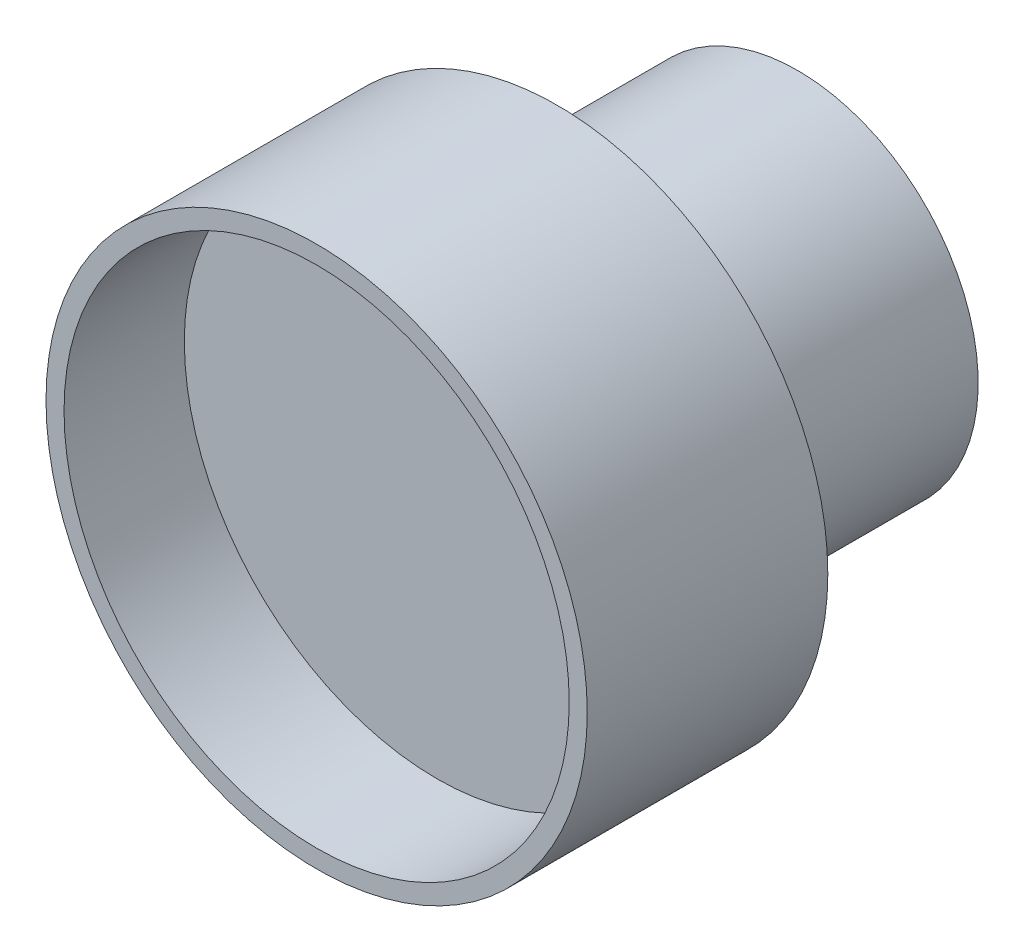
SolidWorks part; units mm, degrees
ref_plane "Front Plane" through (0, 0, 0) normal (0, 0, 1) x (1, 0, 0)
ref_plane "Top Plane" through (0, 0, 0) normal (0, 1, 0) x (1, 0, 0)
ref_plane "Right Plane" through (0, 0, 0) normal (1, 0, 0) x (0, 0, -1)
sketch "Sketch1" plane through (0, 0, 0) normal (0, 0, 1) x (1, 0, 0)
  circle A0 centre (0, 0) radius 22.5
extrude "Boss-Extrude3" add sketch "Sketch1" along normal blind 20
sketch "Sketch4" plane through (0, 0, 20) normal (0, 0, 1) x (1, 0, 0)
  circle A0 centre (0, 0) radius 21
extrude "Cut-Extrude2" cut sketch "Sketch4" against normal blind 10
sketch "Sketch5" plane through (0, 0, 0) normal (0, 0, -1) x (-1, 0, 0)
  circle A1 centre (0, 0) radius 15
extrude "Boss-Extrude4" add sketch "Sketch5" along normal blind 20
sketch "Sketch6" plane through (0, 0, -20) normal (0, 0, -1) x (-1, 0, 0)
  circle A0 centre (0, 0) radius 10
extrude "Cut-Extrude4" cut sketch "Sketch6" against normal blind 20 contours A0
